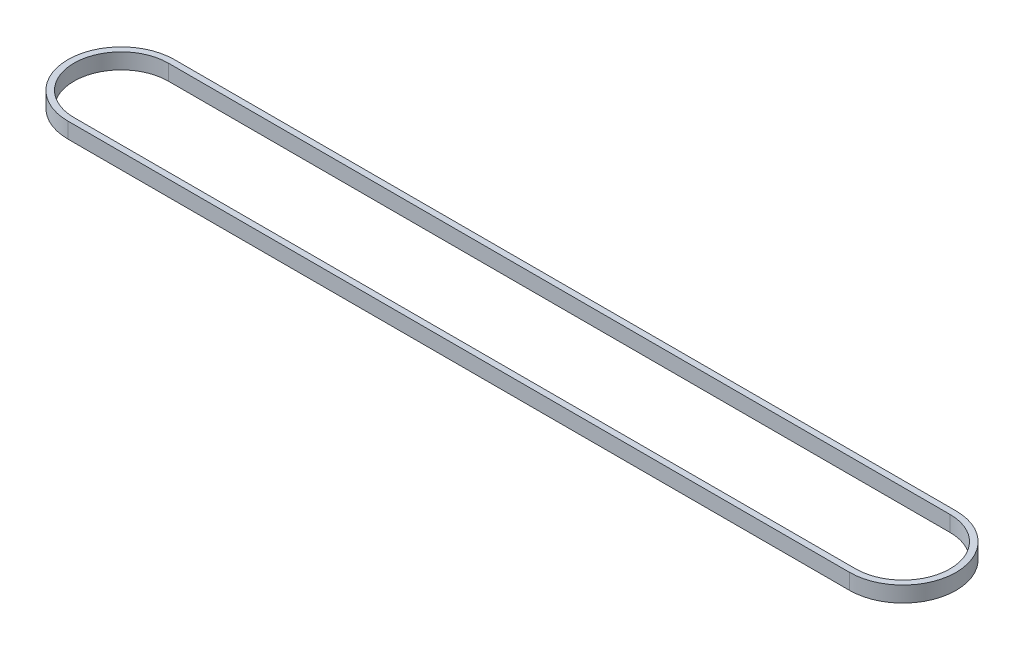
SolidWorks part; units mm, degrees
material "Rubber"
ref_plane "Front Plane" through (0, 0, 0) normal (0, 0, 1) x (1, 0, 0)
ref_plane "Top Plane" through (0, 0, 0) normal (0, 1, 0) x (1, 0, 0)
ref_plane "Right Plane" through (0, 0, 0) normal (1, 0, 0) x (0, 0, -1)
sketch "Sketch1" plane through (0, 0, 0) normal (0, 1, 0) x (1, 0, 0)
  line L0 (0, 28.65) -> (450, 28.65)
  line L1 (0, -28.65) -> (450, -28.65)
  line L2 (0, 30.65) -> (450, 30.65)
  line L3 (0, -30.65) -> (450, -30.65)
  line L4 (0, 27.15) -> (450, 27.15)
  line L5 (0, -27.15) -> (450, -27.15)
  arc A0 (0, 28.65) -> (0, -28.65) centre (0, 0) ccw
  arc A1 (450, -28.65) -> (450, 28.65) centre (450, 0) ccw
  arc A2 (450, -30.65) -> (450, 30.65) centre (450, 0) ccw
  arc A3 (0, 30.65) -> (0, -30.65) centre (0, 0) ccw
  arc A4 (450, -27.15) -> (450, 27.15) centre (450, 0) ccw
  arc A5 (0, 27.15) -> (0, -27.15) centre (0, 0) ccw
  dimension "D1" = 57.3
  dimension "D2" = 57.3
  dimension "D3" = 450
  dimension "D4" = 2
  dimension "D5" = 1.5
extrude "Boss-Extrude1" add sketch "Sketch1" along normal blind 9 contours L1 A1 L0 A0 A5 L4 A4 L5 | L2 A3 L3 A2 A1 L1 A0 L0
